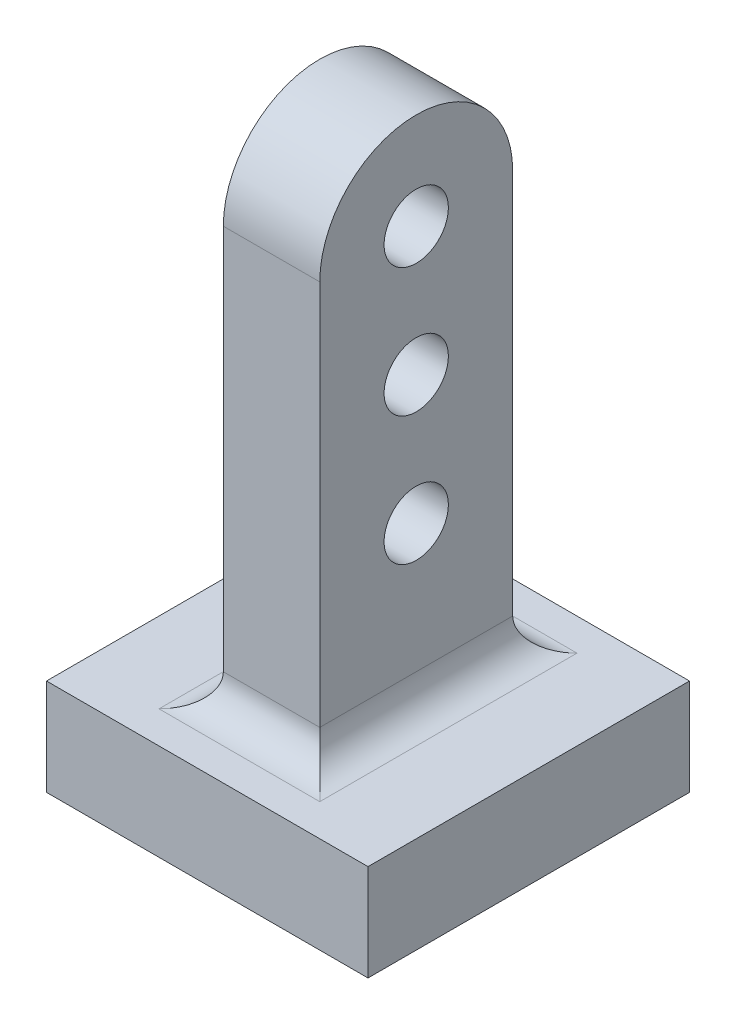
SolidWorks part; units mm, degrees
ref_plane "Front Plane" through (0, 0, 0) normal (0, 0, 1) x (1, 0, 0)
ref_plane "Top Plane" through (0, 0, 0) normal (0, 1, 0) x (1, 0, 0)
ref_plane "Right Plane" through (0, 0, 0) normal (1, 0, 0) x (0, 0, -1)
sketch "Sketch1" plane through (0, 0, 0) normal (0, 1, 0) x (1, 0, 0)
  line L1 (-5, -5) -> (5, -5)
  line L2 (-5, -5) -> (-5, 5)
  line L3 (-5, 5) -> (5, 5)
  line L4 (5, -5) -> (5, 5)
  point P4 (-5, 0)
  point P6 (0, 5)
  dimension "D1" = 10
extrude "Boss-Extrude1" add sketch "Sketch1" along normal blind 3
sketch "Sketch2" plane through (0, 0, 0) normal (1, 0, 0) x (0, 0, -1)
  line L0 (-3, 3) -> (-3, 16)
  line L1 (-5, 3) -> (5, 3) construction
  line L2 (-3, 3) -> (3, 3)
  line L3 (3, 3) -> (3, 16)
  circle A0 centre (0, 16) radius 1
  arc A1 (-3, 16) -> (3, 16) centre (0, 16) cw
  circle A2 centre (0, 12) radius 1
  circle A3 centre (0, 8) radius 1
  point P12 (0, 3)
  point P13 (0, 0)
  point P14 (0, 12.9969)
  point P15 (0, 12.1499)
  point P16 (0, 8.6034)
  point P17 (0, 12)
  point P18 (0, 0)
  point P19 (0, 0)
  point P20 (0, 0)
  dimension "D1" = 2
  dimension "D2" = 2
  dimension "D3" = 12
  dimension "D4" = 4
  dimension "D5" = 4
extrude "Boss-Extrude2" add sketch "Sketch2" along normal mid plane 3
fillet "Fillet1" radius 1 4 edges at (0, 3, -3) (-1.5, 3, 0) (0, 3, 3) (1.5, 3, 0)
